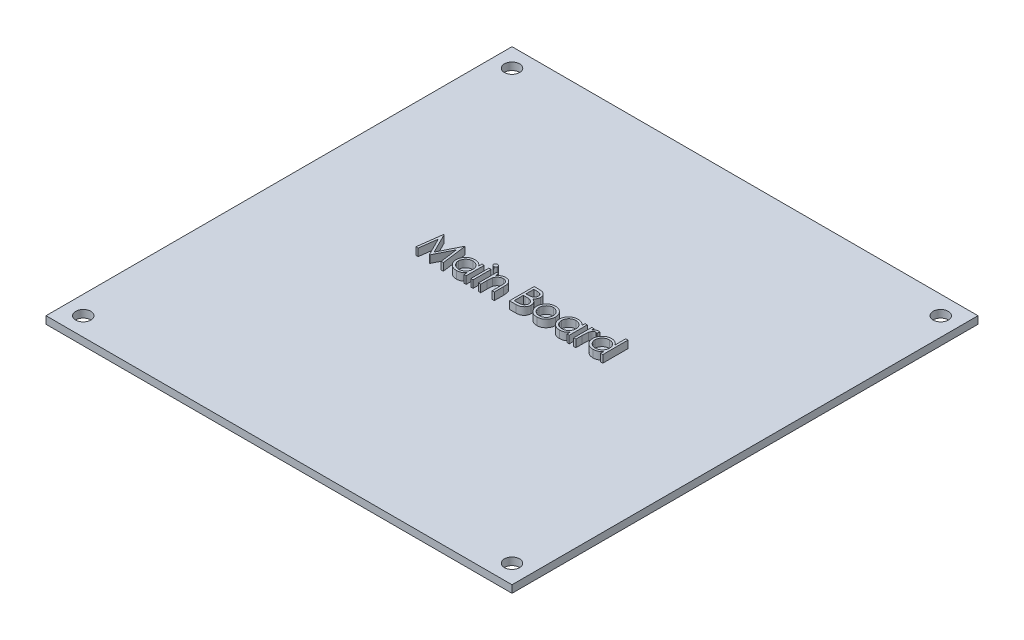
SolidWorks part; units mm, degrees
ref_plane "Front Plane" through (0, 0, 0) normal (0, 0, 1) x (1, 0, 0)
ref_plane "Top Plane" through (0, 0, 0) normal (0, 1, 0) x (1, 0, 0)
ref_plane "Right Plane" through (0, 0, 0) normal (1, 0, 0) x (0, 0, -1)
sketch "Sketch18" plane through (0, 0, 0) normal (0, 1, 0) x (1, 0, 0)
  line L1 (50, -50) -> (-50, -50)
  line L2 (50, -50) -> (50, 50)
  line L3 (50, 50) -> (-50, 50)
  line L4 (-50, -50) -> (-50, 50)
  line L5 (50, -50) -> (-50, 50) construction
  line L6 (50, 50) -> (-50, -50) construction
  point P0 (0, 0)
  dimension "D1" = 100
  dimension "D2" = 100
extrude "Boss-Extrude6" add sketch "Sketch18" along normal blind 1.6
hole_wizard "#4 Clearance Hole3" positions "Sketch23" profile "Sketch22" hole size "#4" standard "ANSI Inch" end condition through all
sketch "Sketch23" plane through (0, 1.6, 0) normal (0, 1, 0) x (1, 0, 0)
  line L0 (50, 50) -> (-50, 50) construction
  line L1 (-50, 50) -> (-50, -50) construction
  line L2 (50, -50) -> (50, 50) construction
  line L3 (-50, -50) -> (50, -50) construction
  point P0 (-46, 46)
  point P2 (46, 46)
  point P4 (46, -46)
  point P6 (-46, -46)
  point P19 (45.6335, 50)
  point P20 (0, 0)
  dimension "D1" = 4
  dimension "D2" = 4
  dimension "D3" = 4
  dimension "D4" = 4
  dimension "D5" = 4
  dimension "D6" = 4
  dimension "D7" = 4
  dimension "D8" = 4
sketch "Sketch22" plane through (-46, 1.6, -46) normal (1, 0, 0) x (0, 0, 1)
  line L0 (0, 0) -> (0, 1.6)
  line L1 (0, 1.6) -> (1.6319, 1.6)
  line L2 (1.6319, 1.6) -> (1.6319, 0)
  line L5 (1.6319, 0) -> (0, 0)
  line L11 (0, -6.35) -> (0, 107.95) construction
  dimension "Thru Hole Dia." = 3.2639
  dimension "Thru Hole Depth" = 1.6
sketch "Sketch24" plane through (0, 1.6, 0) normal (0, 1, 0) x (1, 0, 0)
  text T0 "Main Board" font "Century Gothic" height in points 20
extrude "Boss-Extrude7" add sketch "Sketch24" along normal blind 1.6
